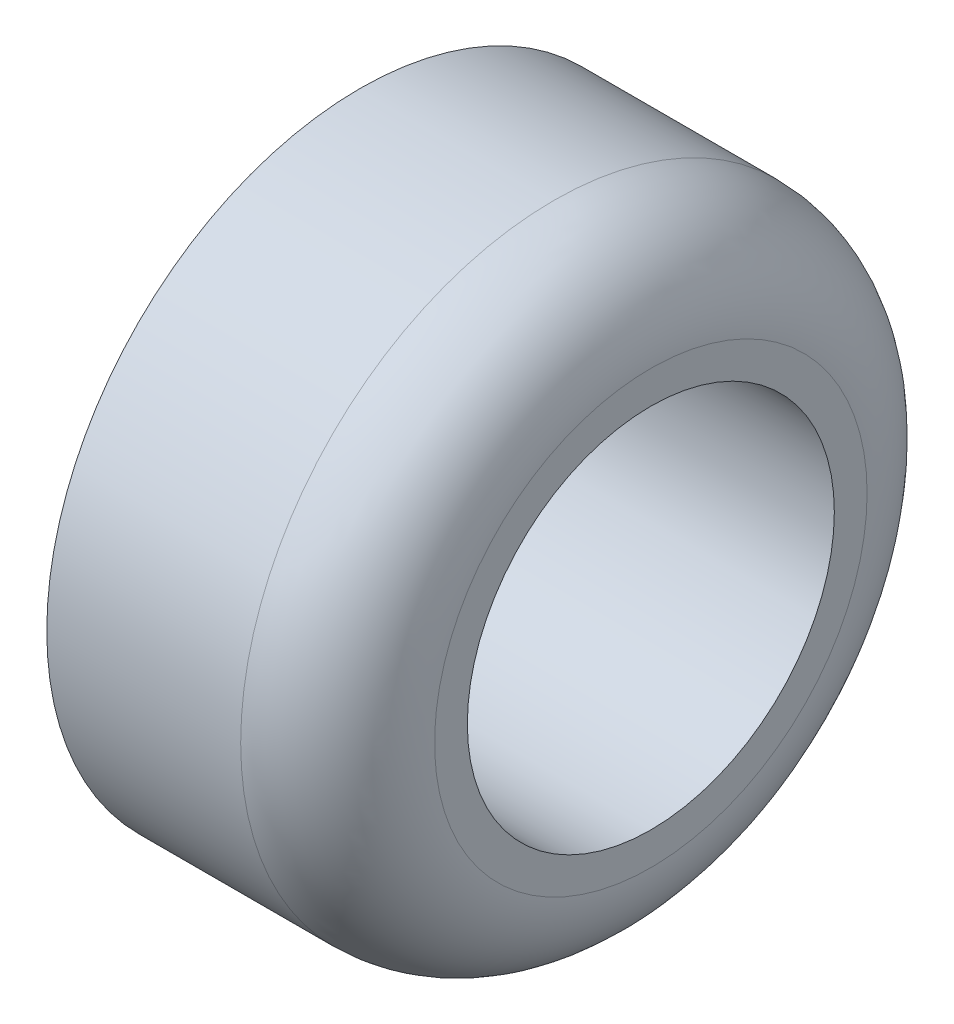
SolidWorks part; units mm, degrees
material "Rubber"
ref_plane "Front Plane" through (0, 0, 0) normal (0, 0, 1) x (1, 0, 0)
ref_plane "Top Plane" through (0, 0, 0) normal (0, 1, 0) x (1, 0, 0)
ref_plane "Right Plane" through (0, 0, 0) normal (1, 0, 0) x (0, 0, -1)
sketch "Sketch2" plane through (0, 0, 0) normal (1, 0, 0) x (0, 0, -1)
  circle A0 centre (0, 0) radius 4.2672
  circle A1 centre (0, 0) radius 2.5
  dimension "D1" = 8.5344
  dimension "D2" = 5
extrude "Boss-Extrude1" add sketch "Sketch2" against normal blind 3.9624
fillet "Fillet2" radius 1.3208 1 edges at (0, 0, -4.2672)
